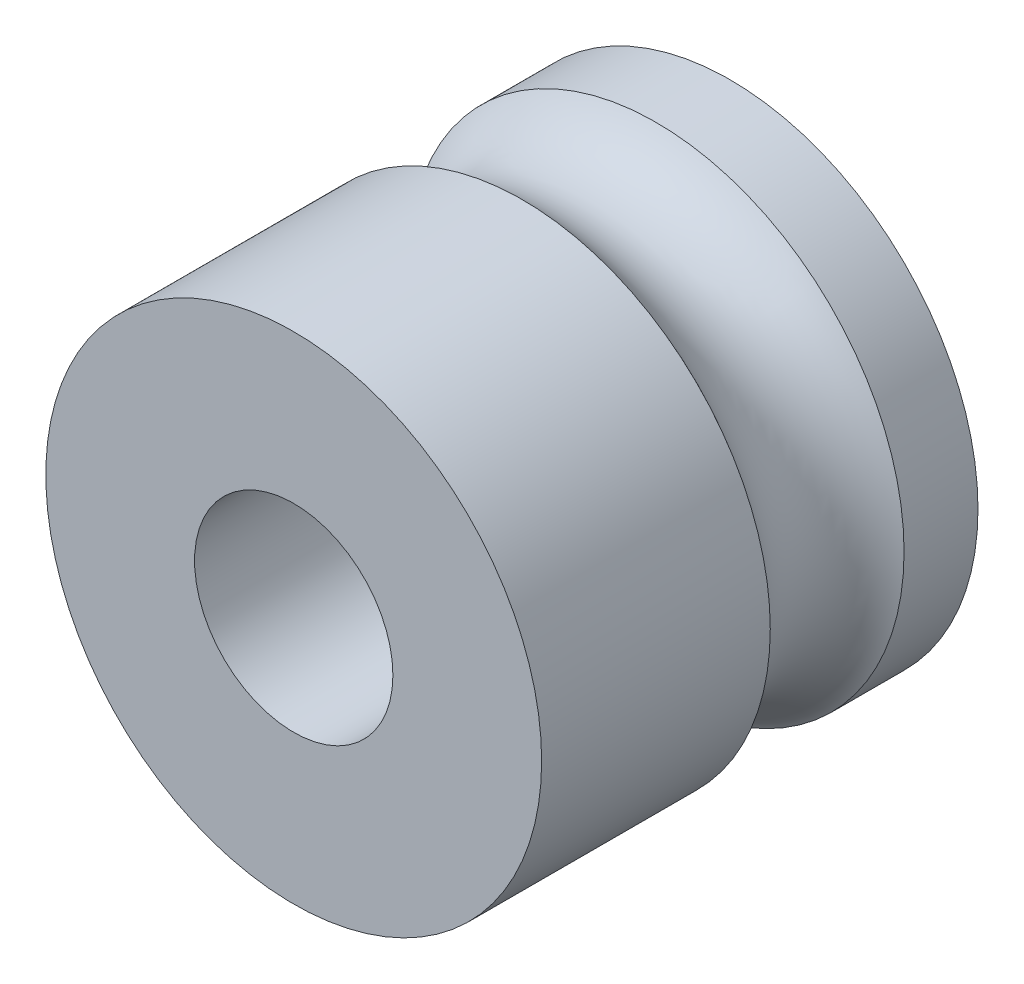
SolidWorks part; units mm, degrees
ref_plane "Front Plane" through (0, 0, 0) normal (0, 0, 1) x (1, 0, 0)
ref_plane "Top Plane" through (0, 0, 0) normal (0, 1, 0) x (1, 0, 0)
ref_plane "Right Plane" through (0, 0, 0) normal (1, 0, 0) x (0, 0, -1)
sketch "Sketch1" plane through (0, 0, 0) normal (0, 1, 0) x (1, 0, 0)
  line L0 (6.25, -1.8635) -> (6.25, 0)
  line L1 (6.25, 0) -> (2.5, 0)
  line L2 (2.5, 0) -> (2.5, -11)
  line L3 (2.5, -11) -> (6.25, -11)
  line L4 (6.25, -11) -> (6.25, -5.2365)
  line L5 (0, 0) -> (0, -11) construction
  arc A0 (6.25, -5.2365) -> (6.25, -1.8635) centre (7.325, -3.55) cw
revolve "Revolve1" add sketch "Sketch1" angle 360 about L5
ref_plane "Plane1" through (0, 0, 5.2365) normal (0, 0, 1) x (1, 0, 0)
ref_plane "Plane2" through (0, 0, 1.8635) normal (0, 0, 1) x (1, 0, 0)
ref_plane "Plane3" through (0, 0, 3.55) normal (0, 0, 1) x (1, 0, 0)
